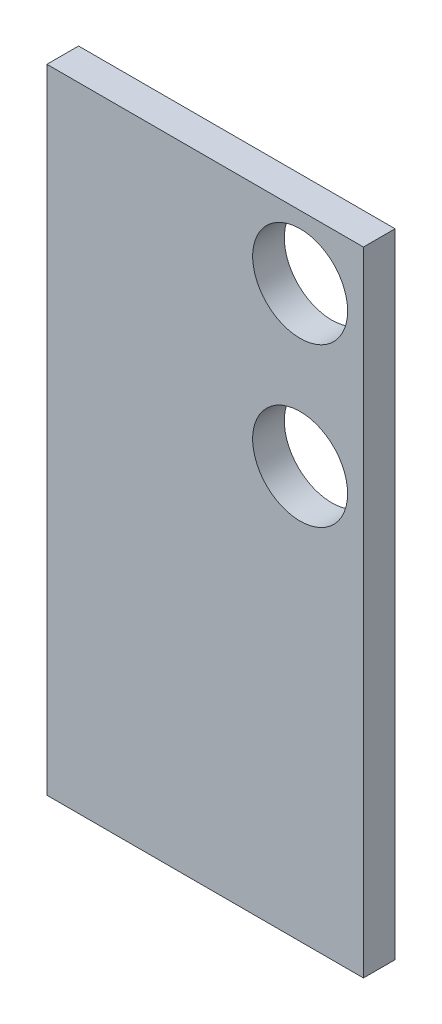
SolidWorks part; units mm, degrees
ref_plane "前视基准面" through (0, 0, 0) normal (0, 0, 1) x (1, 0, 0)
ref_plane "上视基准面" through (0, 0, 0) normal (0, 1, 0) x (1, 0, 0)
ref_plane "右视基准面" through (0, 0, 0) normal (1, 0, 0) x (0, 0, -1)
sketch "草图1" plane through (0, 0, 0) normal (0, 0, 1) x (1, 0, 0)
  line L0 (5.0943, 10) -> (5.0943, -10) construction
  line L1 (7.0943, 10) -> (-2.9057, 10)
  line L2 (7.0943, 10) -> (7.0943, -10)
  line L3 (7.0943, -10) -> (-2.9057, -10)
  line L4 (-2.9057, 10) -> (-2.9057, -10)
  circle A0 centre (5.0943, 8) radius 1.5
  circle A1 centre (5.0943, 3) radius 1.5
  point P0 (0, 0)
  dimension "D3" = 5
  dimension "D1" = 10
  dimension "D2" = 20
  dimension "D4" = 2
  dimension "D5" = 2
extrude "凸台-拉伸1" add sketch "草图1" along normal blind 1
